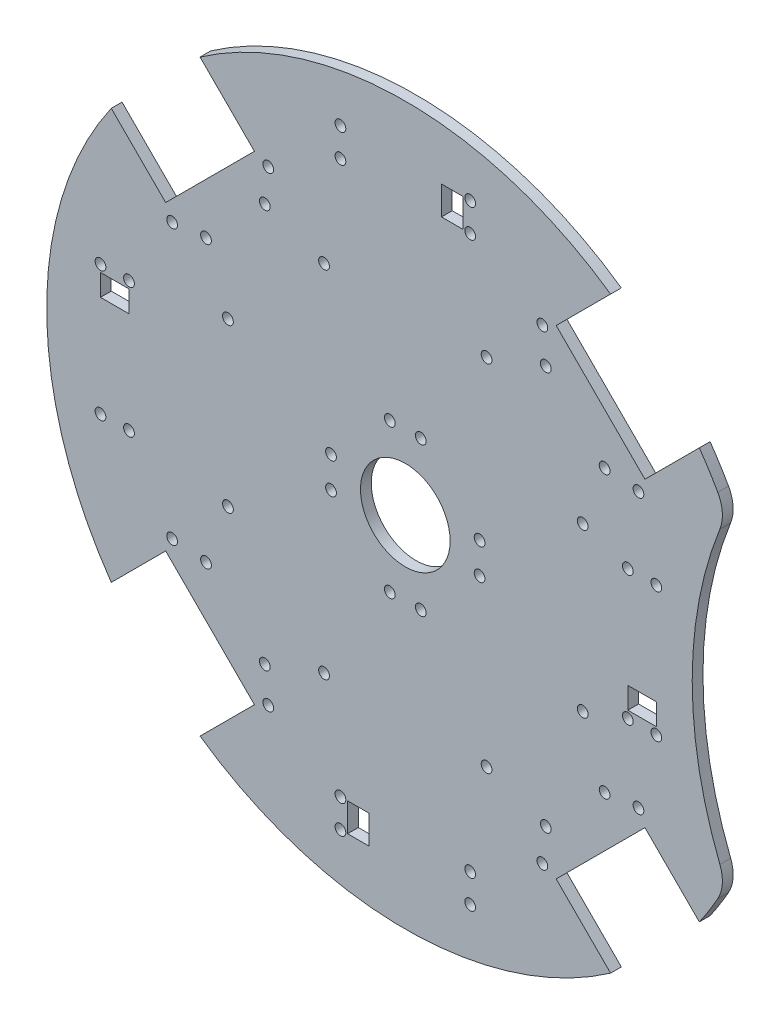
SolidWorks part; units mm, degrees
ref_plane "Alzado" through (0, 0, 0) normal (0, 0, 1) x (1, 0, 0)
ref_plane "Planta" through (0, 0, 0) normal (0, 1, 0) x (1, 0, 0)
ref_plane "Vista lateral" through (0, 0, 0) normal (1, 0, 0) x (0, 0, -1)
sketch "Croquis1" plane through (0, 0, 0) normal (0, 0, 1) x (1, 0, 0)
  circle A0 centre (0, 0) radius 100
  dimension "D1" = 200
extrude "Saliente-Extruir1" add sketch "Croquis1" along normal blind 3
sketch "Croquis3" plane through (0, 0, 3) normal (0, 0, 1) x (1, 0, 0)
  line L0 (0, 0) -> (190, 0) construction
  circle A0 centre (190, 0) radius 110
  dimension "D1" = 220
  dimension "D2" = 190
extrude "Cortar-Extruir1" cut sketch "Croquis3" against normal blind 3
fillet "Redondeo1" radius 10 2 edges at (89.4737, -44.6594, 1.5) (89.4737, 44.6594, 1.5)
sketch "Croquis4" plane through (0, 0, 3) normal (0, 0, 1) x (1, 0, 0)
  line L0 (-100, 0) -> (80, 0) construction
  line L1 (0, 0) -> (0, -100) construction
  line L2 (-54.4472, -54.4472) -> (-51.6188, -51.6188) construction
  line L3 (-58.3363, -83.085) -> (-83.085, -58.3363)
  line L4 (-66.8216, 42.0729) -> (-42.0729, 66.8216)
  line L5 (-83.085, -58.3363) -> (-66.8216, -42.0729)
  line L6 (-58.3363, -83.085) -> (-42.0729, -66.8216)
  line L7 (-42.0729, -66.8216) -> (-66.8216, -42.0729)
  line L8 (-58.3363, 83.085) -> (-42.0729, 66.8216)
  line L9 (-83.085, 58.3363) -> (-58.3363, 83.085)
  line L10 (-83.085, 58.3363) -> (-66.8216, 42.0729)
  line L11 (42.0729, 66.8216) -> (66.8216, 42.0729)
  line L12 (83.085, 58.3363) -> (66.8216, 42.0729)
  line L13 (58.3363, 83.085) -> (83.085, 58.3363)
  line L14 (58.3363, 83.085) -> (42.0729, 66.8216)
  line L15 (66.8216, -42.0729) -> (42.0729, -66.8216)
  line L16 (58.3363, -83.085) -> (42.0729, -66.8216)
  line L17 (83.085, -58.3363) -> (58.3363, -83.085)
  line L18 (83.085, -58.3363) -> (66.8216, -42.0729)
  arc A0 (87.1345, 49.0671) -> (87.1345, -49.0671) centre (0, 0) ccw construction
  arc A1 (87.7193, 40.4803) -> (87.7193, -40.4803) centre (190, 0) ccw construction
  circle A2 centre (-65.0185, -38.2191) radius 1.5
  circle A3 centre (-49.4621, -22.6628) radius 1.5
  circle A4 centre (-22.6628, -49.4621) radius 1.5
  circle A5 centre (-38.2191, -65.0185) radius 1.5
  circle A6 centre (-22.6628, 49.4621) radius 1.5
  circle A7 centre (-38.2191, 65.0185) radius 1.5
  circle A8 centre (-49.4621, 22.6628) radius 1.5
  circle A9 centre (-65.0185, 38.2191) radius 1.5
  circle A10 centre (49.4621, 22.6628) radius 1.5
  circle A11 centre (65.0185, 38.2191) radius 1.5
  circle A12 centre (22.6628, 49.4621) radius 1.5
  circle A13 centre (38.2191, 65.0185) radius 1.5
  circle A14 centre (22.6628, -49.4621) radius 1.5
  circle A15 centre (38.2191, -65.0185) radius 1.5
  circle A16 centre (49.4621, -22.6628) radius 1.5
  circle A17 centre (65.0185, -38.2191) radius 1.5
  circle A18 centre (0, 0) radius 12.5
  point P64 (0, 0)
  dimension "D5" = 3
  dimension "D6" = 3
  dimension "D7" = 3
  dimension "D8" = 22
  dimension "D9" = 3
  dimension "D10" = 37.9
  dimension "D11" = 22
  dimension "D12" = 37.9
  dimension "D14" = 54.4068
  dimension "D17" = 25
  dimension "D1" = 35
  dimension "D2" = 23
  dimension "D3" = 23
  dimension "D4" = 17.5
  dimension "D13" = 4
  dimension "D15" = 77
  dimension "D16" = 4
extrude "Cortar-Extruir2" cut sketch "Croquis4" against normal through all
sketch "Croquis6" plane through (0, 0, 3) normal (0, 0, 1) x (1, 0, 0)
  line L0 (0, 100) -> (0, 85) construction
  line L1 (70, -16.59) -> (70, -16.09) construction
  line L2 (70, 18.09) -> (62.05, 18.09) construction
  line L3 (-16.59, 85) -> (16.59, 85) construction
  line L4 (70, -16.09) -> (62.05, -16.09)
  line L5 (70, -16.09) -> (70, -10.09)
  line L8 (16.09, 85) -> (10.09, 85)
  line L9 (16.09, 85) -> (16.09, 77.05)
  line L10 (16.09, 77.05) -> (10.09, 77.05)
  line L11 (10.09, 85) -> (10.09, 77.05)
  line L14 (-16.09, -77.05) -> (-10.09, -77.05)
  line L15 (-10.09, -85) -> (-10.09, -77.05)
  line L16 (-16.09, -85) -> (-16.09, -77.05)
  line L17 (-16.09, -85) -> (-10.09, -85)
  line L18 (70, -10.09) -> (62.05, -10.09)
  line L19 (62.05, -16.09) -> (62.05, -10.09)
  line L20 (-77.05, 16.09) -> (-77.05, 10.09)
  line L21 (-85, 10.09) -> (-77.05, 10.09)
  line L22 (-85, 16.09) -> (-77.05, 16.09)
  line L23 (-85, 16.09) -> (-85, 10.09)
  line L24 (77.05, -16.09) -> (77.05, -10.09) [skipped]
  line L25 (85, -10.09) -> (77.05, -10.09) [skipped]
  line L26 (85, -16.09) -> (77.05, -16.09) [skipped]
  line L27 (85, -16.09) -> (85, -10.09) [skipped]
  arc A0 (87.7193, 40.4803) -> (87.7193, -40.4803) centre (190, 0) ccw construction
  circle A1 centre (70, 18.09) radius 1.5
  circle A2 centre (62.05, 18.09) radius 1.5
  circle A3 centre (62.05, -18.09) radius 1.5
  arc A4 (57.2451, 81.9939) -> (-57.2451, 81.9939) centre (0, 0) ccw construction
  circle A5 centre (-18.09, 85) radius 1.5
  circle A6 centre (-18.09, 77.05) radius 1.5
  circle A7 centre (18.09, 85) radius 1.5
  circle A8 centre (18.09, 77.05) radius 1.5
  circle A9 centre (70, -18.09) radius 1.5
  circle A14 centre (18.09, -77.05) radius 1.5
  circle A15 centre (18.09, -85) radius 1.5
  circle A16 centre (-18.09, -85) radius 1.5
  circle A17 centre (-18.09, -77.05) radius 1.5
  circle A18 centre (-77.05, -18.09) radius 1.5
  circle A19 centre (-85, -18.09) radius 1.5
  circle A20 centre (-85, 18.09) radius 1.5
  circle A21 centre (-77.05, 18.09) radius 1.5
  circle A22 centre (77.05, 18.09) radius 1.5 [skipped]
  circle A23 centre (85, 18.09) radius 1.5 [skipped]
  circle A24 centre (85, -18.09) radius 1.5 [skipped]
  circle A25 centre (77.05, -18.09) radius 1.5 [skipped]
  point P66 (0, 0)
  point P77 (0, 0)
  dimension "D5" = 3
  dimension "D6" = 3
  dimension "D7" = 3
  dimension "D8" = 3
  dimension "D9" = 7.95
  dimension "D10" = 36.18
  dimension "D11" = 0
  dimension "D12" = 36.18
  dimension "D13" = 120
  dimension "D14" = 3
  dimension "D15" = 3
  dimension "D16" = 3
  dimension "D2" = 7.95
  dimension "D3" = 36.18
  dimension "D21" = 36.18
  dimension "D20" = 7.95
  dimension "D22" = 7.95
  dimension "D4" = 2
  dimension "D17" = 6
  dimension "D19" = 7.95
  dimension "D23" = 6
  dimension "D24" = 7.95
  dimension "D25" = 2
  dimension "D26" = 8
  dimension "D27" = 4
extrude "Cortar-Extruir3" cut sketch "Croquis6" against normal blind 10
sketch "Croquis8" plane through (0, 0, 3) normal (0, 0, 1) x (1, 0, 0)
  line L0 (-65.0185, 38.2191) -> (-49.4621, 22.6628) construction
  line L1 (-38.2191, 65.0185) -> (-22.6628, 49.4621) construction
  line L2 (-55.5786, 39.1737) -> (-62.6497, 46.2448) construction
  line L3 (-55.5786, 39.1737) -> (-20.7182, 4.3134) construction
  line L4 (-55.5786, 39.1737) -> (-39.1737, 55.5786) construction
  line L5 (-66.8216, 42.0729) -> (-42.0729, 66.8216) construction
  line L6 (-39.1737, 55.5786) -> (-46.2448, 62.6497) construction
  line L7 (-39.1737, 55.5786) -> (-4.3134, 20.7182) construction
  line L8 (-4.3134, 20.7182) -> (-20.7182, 4.3134) construction
  line L9 (-20.7182, 4.3134) -> (-18.8249, 2.5768) construction
  circle A0 centre (-55.5786, 39.1737) radius 1.5
  circle A1 centre (-39.1737, 55.5786) radius 1.5
  circle A2 centre (-20.7182, 4.3134) radius 1.5
  circle A3 centre (-4.3134, 20.7182) radius 1.5
  circle A5 centre (39.1737, 55.5786) radius 1.5
  circle A6 centre (55.5786, 39.1737) radius 1.5
  circle A7 centre (20.7182, 4.3134) radius 1.5
  circle A8 centre (4.3134, 20.7182) radius 1.5
  circle A9 centre (55.5786, -39.1737) radius 1.5
  circle A10 centre (39.1737, -55.5786) radius 1.5
  circle A11 centre (4.3134, -20.7182) radius 1.5
  circle A12 centre (20.7182, -4.3134) radius 1.5
  circle A13 centre (-39.1737, -55.5786) radius 1.5
  circle A14 centre (-55.5786, -39.1737) radius 1.5
  circle A15 centre (-20.7182, -4.3134) radius 1.5
  circle A16 centre (-4.3134, -20.7182) radius 1.5
  point P50 (0, 0)
  dimension "D1" = 3
  dimension "D2" = 3
  dimension "D3" = 3
  dimension "D4" = 3
  dimension "D5" = 23.2
  dimension "D6" = 49.3
  dimension "D7" = 10
  dimension "D8" = 10
  dimension "D10" = 4
extrude "Cortar-Extruir5" cut sketch "Croquis8" against normal through all
